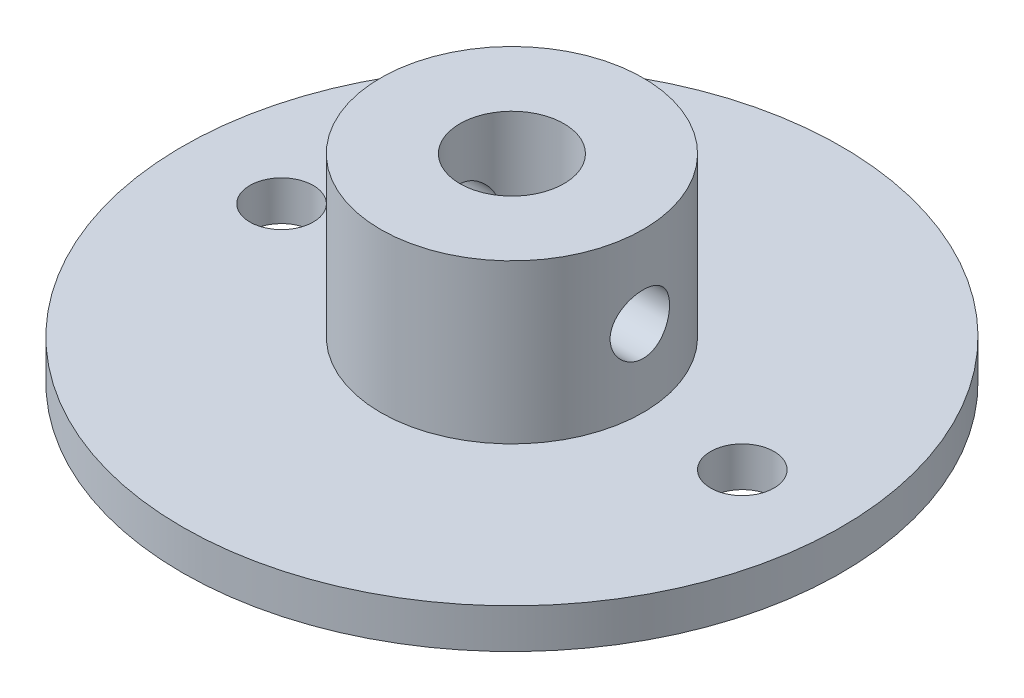
SolidWorks part; units mm, degrees
ref_plane "Front Plane" through (0, 0, 0) normal (0, 0, 1) x (1, 0, 0)
ref_plane "Top Plane" through (0, 0, 0) normal (0, 1, 0) x (1, 0, 0)
ref_plane "Right Plane" through (0, 0, 0) normal (1, 0, 0) x (0, 0, -1)
sketch "Sketch1" plane through (0, 0, 0) normal (0, 1, 0) x (1, 0, 0)
  circle A0 centre (0, 0) radius 16.63
  circle A1 centre (0, 0) radius 2.625
  circle A2 centre (0, 0) radius 4.8
  dimension "D1" = 33.26
  dimension "D2" = 5.25
  dimension "D3" = 9.6
extrude "Boss-Extrude2" add sketch "Sketch1" along normal blind 2 contours A0 A2 | A2 A1
sketch "Sketch4" plane through (0, 2, 0) normal (0, 1, 0) x (1, 0, 0)
  circle A0 centre (11.625, 0) radius 1.6
  circle A1 centre (0, 0) radius 2.625 construction
  dimension "D1" = 3.2
  dimension "D2" = 11.625
sketch "Sketch5" plane through (0, 2, 0) normal (0, 1, 0) x (1, 0, 0)
  circle A0 centre (0, 0) radius 6.625
  circle A1 centre (0, 0) radius 2.625
  dimension "D1" = 5.25
  dimension "D2" = 13.25
extrude "Boss-Extrude3" add sketch "Sketch5" along normal blind 8
extrude "Cut-Extrude1" cut sketch "Sketch4" against normal blind 8
pattern_circular "CirPattern1" count 2 over 360 about axis through (0, 0, 0) along (0, 1, 0) of "Cut-Extrude1"
sketch "Sketch6" plane through (0, 0, 0) normal (1, 0, 0) x (0, 0, -1)
  line L0 (0, 10) -> (0, 0) construction
  circle A0 centre (0, 5.8664) radius 1.5
  dimension "D1" = 3
extrude "Cut-Extrude2" cut sketch "Sketch6" against normal blind 8 and the other way blind 10
